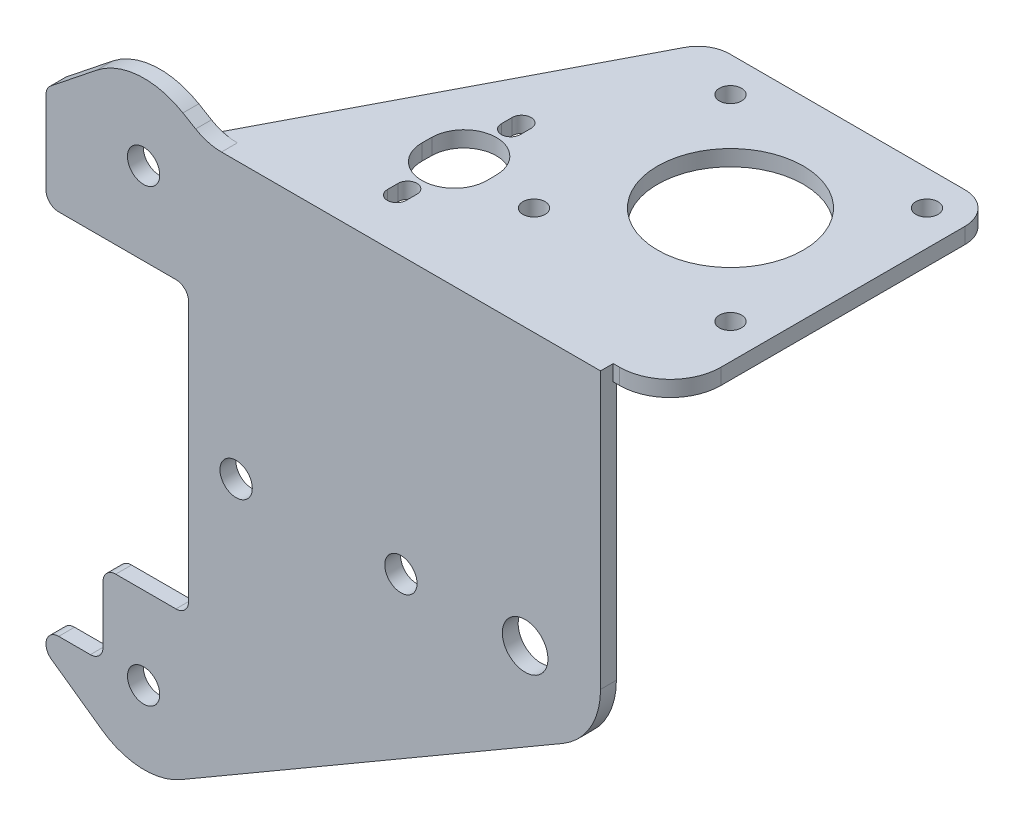
SolidWorks part; units mm, degrees
ref_plane "Alzado" through (0, 0, 0) normal (0, 0, 1) x (1, 0, 0)
ref_plane "Planta" through (0, 0, 0) normal (0, 1, 0) x (1, 0, 0)
ref_plane "Vista lateral" through (0, 0, 0) normal (1, 0, 0) x (0, 0, -1)
ref_plane "Plano1" through (0, 43.5264, 0) normal (0, 1, 0) x (1, 0, 0)
sketch "Croquis1" plane through (0, 43.5264, 0) normal (0, 1, 0) x (1, 0, 0)
  line L0 (24.7604, 29.4) -> (51.3229, 29.4)
  line L1 (51.3229, 29.4) -> (51.3229, 80.4)
  line L2 (51.3229, 80.4) -> (24.7604, 29.4)
extrude "Saliente-Extruir1" add sketch "Croquis1" against normal blind 2.5
sketch "Croquis2" plane through (51.3229, 0, 0) normal (1, 0, 0) x (0, 0, -1)
  line L0 (29.4, 43.5264) -> (80.4, 43.5264)
  line L1 (80.4, 43.5264) -> (80.4, 41.0264)
  line L2 (80.4, 41.0264) -> (29.4, 41.0264)
  line L3 (29.4, 41.0264) -> (29.4, 43.5264)
extrude "Saliente-Extruir2" add sketch "Croquis2" along normal blind 36.1771
sketch "Croquis3" plane through (0, 0, -29.4) normal (0, 0, 1) x (1, 0, 0)
  line L0 (0, -38.6072) -> (0, 38.4886)
  line L1 (0, 38.4886) -> (14.4887, 50.0414)
  line L2 (14.4887, 50.0414) -> (25.5, 43.5264)
  line L3 (25.5, 43.5264) -> (87.5, 43.5264)
  line L4 (87.5, 43.5264) -> (87.5, -6.9002)
  line L5 (87.5, -6.9002) -> (14.887, -49.1628)
  line L6 (14.887, -49.1628) -> (0, -38.6072)
extrude "Saliente-Extruir3" add sketch "Croquis3" along normal blind 2.5
sketch "Croquis4" plane through (87.5, 0, 0) normal (1, 0, 0) x (0, 0, -1)
  line L0 (28.9, 43.5264) -> (80.4, 43.5264)
  line L1 (80.4, 43.5264) -> (80.4, 41.0264)
  line L2 (80.4, 41.0264) -> (28.9, 41.0264)
  line L3 (28.9, 41.0264) -> (28.9, 43.5264)
extrude "Saliente-Extruir4" add sketch "Croquis4" along normal blind 9
sketch "Croquis5" plane through (0, 0, -26.9) normal (0, 0, 1) x (1, 0, 0)
  line L0 (0, 22.5) -> (0, -35.5)
  line L1 (0, -35.5) -> (9, -35.5)
  line L2 (9, -35.5) -> (9, -22.5)
  line L3 (9, -22.5) -> (22.5, -22.5)
  line L4 (22.5, -22.5) -> (22.5, 22.5)
  line L5 (22.5, 22.5) -> (0, 22.5)
extrude "Cortar-Extruir1" cut sketch "Croquis5" against normal through all
hole_wizard "Diámetro de taladro Ø5.1 (5.1)1" positions "Croquis10" profile "Croquis9" hole size "Ø5.1" standard "Ansi Metric"
sketch "Croquis10" plane through (0, 0, -26.9) normal (0, 0, 1) x (1, 0, 0)
  point P0 (56, 0)
  point P1 (30, 0)
sketch "Croquis9" plane through (56, 0, -26.9) normal (1, 0, 0) x (0, -1, 0)
  line L0 (0, 0) -> (0, 53.5)
  line L1 (0, 53.5) -> (2.55, 53.5)
  line L2 (2.55, 53.5) -> (2.55, 0)
  line L5 (2.55, 0) -> (0, 0)
  line L11 (0, -6.35) -> (0, 107.95) construction
  dimension "Diámetro de taladro hasta el siguiente" = 5.1
  dimension "Profundidad de taladro hasta el siguiente" = 53.5
hole_wizard "Diámetro de taladro Ø5.1 (5.1)2" positions "Croquis12" profile "Croquis11" hole size "Ø5.1" standard "Ansi Metric"
sketch "Croquis12" plane through (0, 0, -29.4) normal (0, 0, -1) x (-1, 0, 0)
  point P0 (-15.4, -35.5)
  point P1 (-15.4, 35.5)
sketch "Croquis11" plane through (15.4, -35.5, -29.4) normal (1, 0, 0) x (0, 1, 0)
  line L0 (0, 0) -> (0, 2.5)
  line L1 (0, 2.5) -> (2.55, 2.5)
  line L2 (2.55, 2.5) -> (2.55, 0)
  line L5 (2.55, 0) -> (0, 0)
  line L11 (0, -6.35) -> (0, 107.95) construction
  dimension "Diámetro de taladro hasta el siguiente" = 5.1
  dimension "Profundidad de taladro hasta el siguiente" = 2.5
hole_wizard "Diámetro de taladro Ø7.2 (7.2)1" positions "Croquis14" profile "Croquis13" hole size "Ø7.2" standard "Ansi Metric"
sketch "Croquis14" plane through (0, 0, -29.4) normal (0, 0, -1) x (-1, 0, 0)
  point P0 (-75.6, 0)
sketch "Croquis13" plane through (75.6, 0, -29.4) normal (1, 0, 0) x (0, 1, 0)
  line L0 (0, 0) -> (0, 2.5)
  line L1 (0, 2.5) -> (3.6, 2.5)
  line L2 (3.6, 2.5) -> (3.6, 0)
  line L5 (3.6, 0) -> (0, 0)
  line L11 (0, -6.35) -> (0, 107.95) construction
  dimension "Diámetro de taladro hasta el siguiente" = 7.2
  dimension "Profundidad de taladro hasta el siguiente" = 2.5
hole_wizard "Diámetro de taladro Ø23.0 (23)1" positions "Croquis16" profile "Croquis15" hole size "Ø23.0" standard "Ansi Metric"
sketch "Croquis16" plane through (0, 41.0264, 0) normal (0, -1, 0) x (-1, 0, 0)
  point P0 (-75.5, 59.4)
sketch "Croquis15" plane through (75.5, 41.0264, -59.4) normal (1, 0, 0) x (0, 0, -1)
  line L0 (0, 0) -> (0, 9.015)
  line L1 (0, 9.015) -> (11.5, 9.015)
  line L2 (11.5, 9.015) -> (11.5, 0)
  line L5 (11.5, 0) -> (0, 0)
  line L11 (0, -6.35) -> (0, 107.95) construction
  dimension "Diámetro de taladro hasta el siguiente" = 23
  dimension "Profundidad de taladro hasta el siguiente" = 9.015
hole_wizard "Diámetro de taladro Ø3.5 (3.5)1" positions "Croquis18" profile "Croquis17" hole size "Ø3.5" standard "Ansi Metric"
sketch "Croquis18" plane through (0, 41.0264, 0) normal (0, -1, 0) x (-1, 0, 0)
  point P0 (-60, 74.9)
  point P1 (-91, 43.9)
  point P2 (-60, 43.9)
  point P3 (-91, 74.9)
sketch "Croquis17" plane through (60, 41.0264, -74.9) normal (1, 0, 0) x (0, 0, -1)
  line L0 (0, 0) -> (0, 9.015)
  line L1 (0, 9.015) -> (1.75, 9.015)
  line L2 (1.75, 9.015) -> (1.75, 0)
  line L5 (1.75, 0) -> (0, 0)
  line L11 (0, -6.35) -> (0, 107.95) construction
  dimension "Diámetro de taladro hasta el siguiente" = 3.5
  dimension "Profundidad de taladro hasta el siguiente" = 9.015
fillet "Redondeo1" radius 2 8 edges at (0, -35.5, -28.15) (22.5, -22.5, -28.15) (22.5, 22.5, -28.15) (0, -38.6072, -28.15) (9, -22.5, -28.15) (9, -35.5, -28.15) (0, 22.5, -28.15) (0, 38.4886, -28.15)
fillet "Redondeo2" radius 5 2 edges at (96.5, 42.2764, -80.4) (51.3229, 42.2764, -80.4)
fillet "Redondeo3" radius 8 2 edges at (96.5, 42.2764, -28.9) (25.5, 43.5264, -28.15)
fillet "Redondeo4" radius 11.5 1 edges at (14.887, -49.1628, -28.15)
fillet "Redondeo5" radius 12 2 edges at (87.5, -6.9002, -28.15) (14.4887, 50.0414, -28.15)
sketch "Croquis19" plane through (0, 43.5264, 0) normal (0, 1, 0) x (1, 0, 0)
  line L0 (42.256, 44.0078) -> (42.271, 45.5077)
  line L1 (52.5259, 44.0078) -> (52.5109, 45.5077)
  line L2 (47.3909, 34.8565) -> (47.3909, 36.5565) construction
  line L3 (45.9036, 34.8565) -> (45.9036, 36.5565)
  line L4 (48.8782, 34.8565) -> (48.8782, 36.5565)
  line L5 (47.3909, 52.8565) -> (47.3909, 54.5565) construction
  line L6 (45.8986, 52.8565) -> (45.8986, 54.5565)
  line L7 (48.8833, 52.8565) -> (48.8833, 54.5565)
  arc A0 (42.256, 44.0078) -> (52.5259, 44.0078) centre (47.3909, 43.9565) ccw
  arc A1 (52.5109, 45.5077) -> (42.271, 45.5077) centre (47.3909, 45.4565) ccw
  arc A2 (45.9036, 34.8565) -> (48.8782, 34.8565) centre (47.3909, 34.8565) ccw
  arc A3 (48.8782, 36.5565) -> (45.9036, 36.5565) centre (47.3909, 36.5565) ccw
  arc A4 (45.8986, 52.8565) -> (48.8833, 52.8565) centre (47.3909, 52.8565) ccw
  arc A5 (48.8833, 54.5565) -> (45.8986, 54.5565) centre (47.3909, 54.5565) ccw
  point P10 (47.3909, 35.7065)
  point P17 (47.3909, 53.7065)
  point P26 (0, 0)
  point P27 (0, 0)
  point P28 (0, 0)
  point P29 (0, 0)
  point P30 (0, 0)
  point P31 (0, 0)
extrude "Cortar-Extruir2" cut sketch "Croquis19" against normal blind 10
